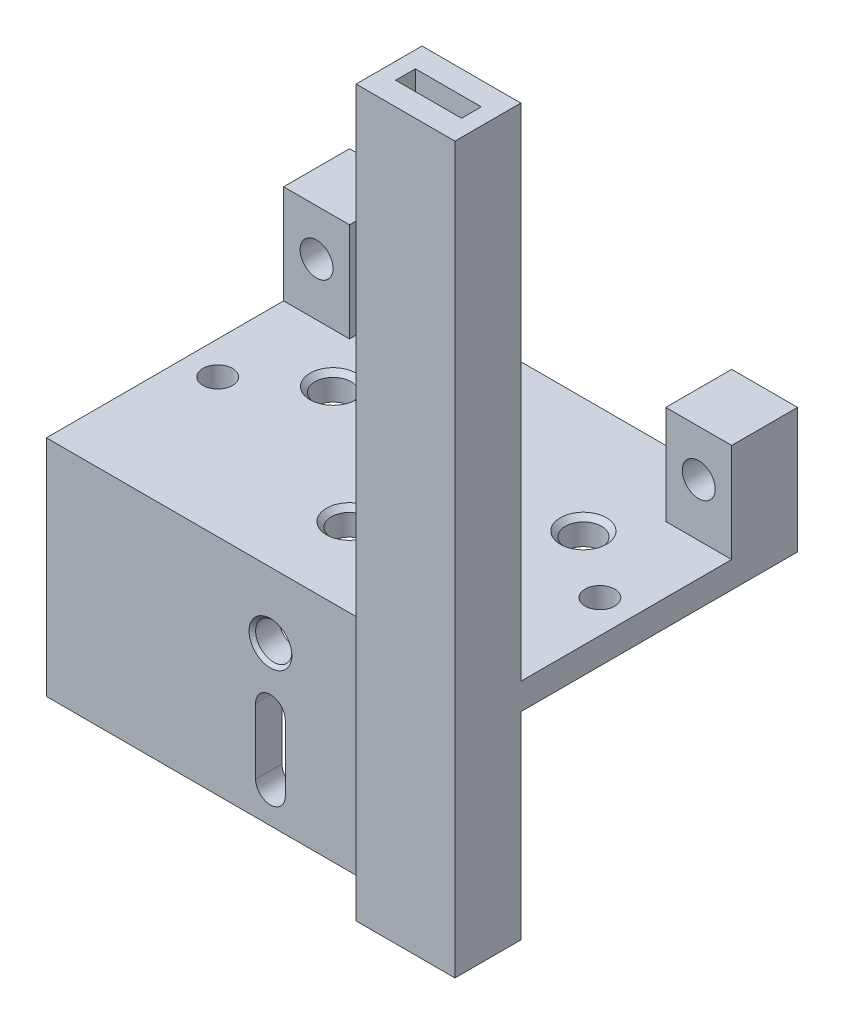
SolidWorks part; units mm, degrees
material "PET"
ref_plane "Front Plane" through (0, 0, 0) normal (0, 0, 1) x (1, 0, 0)
ref_plane "Top Plane" through (0, 0, 0) normal (0, 1, 0) x (1, 0, 0)
ref_plane "Right Plane" through (0, 0, 0) normal (1, 0, 0) x (0, 0, -1)
sketch "Sketch1" plane through (0, 0, 0) normal (0, 1, 0) x (1, 0, 0)
  line L0 (-30, 15) -> (30, 15) construction
  line L2 (-34, 0) -> (-34, 40)
  line L3 (-34, 40) -> (34, 40)
  line L4 (34, 0) -> (34, 40)
  line L5 (0, 0) -> (34, 40) construction
  line L6 (-34, 40) -> (0, 0) construction
  line L7 (-34, 22.5) -> (34, 22.5) construction
  line L8 (-34, 0) -> (-34, -2)
  line L11 (-34, -2) -> (34, -2)
  line L12 (34, -2) -> (34, 0)
  line L13 (-34, 0) -> (34, 0) construction
  line L14 (0, 0) -> (0, 27.8808) construction
  circle A0 centre (-19, 22.5) radius 2.75
  circle A1 centre (19, 22.5) radius 2.75
  circle A3 centre (-29, 15) radius 2.25
  circle A4 centre (29, 15) radius 2.25
  circle A6 centre (0, 6) radius 2.75
  point P0 (0, 0)
  dimension "D5" = 5.5
  dimension "D6" = 5.5
  dimension "D7" = 5.5
  dimension "D8" = 4.5
  dimension "D9" = 4.5
  dimension "D10" = 5
  dimension "D11" = 5
  dimension "D13" = 6
  dimension "D21" = 15
  dimension "D2" = 68
  dimension "D3" = 2
  dimension "D4" = 17.5
  dimension "D12" = 25
  dimension "D17" = 40
  dimension "D18" = 34
  dimension "D20" = 15
extrude "Boss-Extrude1" add sketch "Sketch1" along normal blind 4
sketch "Sketch3" plane through (0, 4, 0) normal (0, 1, 0) x (1, 0, 0)
  line L1 (-34, 40) -> (-24, 40)
  line L2 (-34, 40) -> (-34, 30)
  line L3 (-34, 30) -> (-24, 30)
  line L4 (-24, 40) -> (-24, 30)
  line L5 (34, 40) -> (24, 40)
  line L6 (34, 40) -> (34, 30)
  line L7 (34, 30) -> (24, 30)
  line L8 (24, 40) -> (24, 30)
  dimension "D1" = 10
  dimension "D2" = 10
  dimension "D3" = 10
extrude "Boss-Extrude3" add sketch "Sketch3" along normal blind 15
sketch "Sketch4" plane through (0, 0, -40) normal (0, 0, -1) x (-1, 0, 0)
  line L0 (-24, 19) -> (-34, 5) construction
  line L1 (24, 19) -> (34, 19) construction
  line L2 (24, 19) -> (34, 5) construction
  line L4 (-34, 19) -> (-24, 19) construction
  line L5 (-34, 19) -> (-34, 0) construction
  line L6 (34, 19) -> (34, 0) construction
  circle A0 centre (-29, 12) radius 2.5
  circle A1 centre (29, 12) radius 2.5
  dimension "D3" = 5
  dimension "D4" = 5
  dimension "D5" = 7
  dimension "D1" = 7
extrude "Cut-Extrude1" cut sketch "Sketch4" against normal through all
chamfer "Chamfer1" distance 0.75 angle 45 3 edges at (-19, 4, -19.75) (19, 4, -19.75) (0, 4, -3.25)
sketch "Sketch5" plane through (-34, 0, 0) normal (-1, 0, 0) x (0, 0, 1)
  line L0 (2, 4) -> (2, 0) construction
  line L1 (2, 4) -> (6, 4)
  line L2 (2, 4) -> (2, -30)
  line L3 (2, -30) -> (6, -30)
  line L4 (6, 4) -> (6, -30)
  line L5 (-30, 4) -> (2, 4) construction
  line L6 (-40, 0) -> (2, 0) construction
  dimension "D1" = 30
  dimension "D2" = 4
extrude "Boss-Extrude4" add sketch "Sketch5" against normal up to surface (68 mm away) up to face at (34, 7.6667, -22.6667)
sketch "Sketch7" plane through (0, 0, 2) normal (0, 0, -1) x (-1, 0, 0)
  line L0 (0, -15) -> (0, -25) construction
  line L1 (2.25, -15) -> (2.25, -25)
  line L2 (-2.25, -15) -> (-2.25, -25)
  line L3 (34, 0) -> (-34, 0) construction
  line L4 (0, -6) -> (0, 0) construction
  arc A0 (2.25, -15) -> (-2.25, -15) centre (0, -15) ccw
  arc A1 (-2.25, -25) -> (2.25, -25) centre (0, -25) ccw
  circle A2 centre (0, -6) radius 2.75
  point P3 (0, -20)
  dimension "D1" = 2.25
  dimension "D4" = 5.5
  dimension "D2" = 15
  dimension "D3" = 10
  dimension "D5" = 6
extrude "Cut-Extrude2" cut sketch "Sketch7" against normal through all
chamfer "Chamfer2" distance 0.5 angle 45 1 edges at (0, -3.25, 6)
sketch "Sketch8" plane through (0, -30, 0) normal (0, -1, 0) x (1, 0, 0)
  line L1 (34, 2) -> (19, 2)
  line L2 (34, 2) -> (34, 12)
  line L3 (34, 12) -> (19, 12)
  line L4 (19, 2) -> (19, 12)
  dimension "D1" = 10
  dimension "D2" = 15
extrude "Boss-Extrude5" add sketch "Sketch8" against normal blind 110
sketch "Sketch9" plane through (0, 0, 6) normal (0, 0, 1) x (1, 0, 0)
  line L0 (17, -3) -> (17, -24) construction
  line L1 (19, -3) -> (19, -24)
  line L2 (15, -3) -> (15, -24)
  line L3 (19, 4) -> (19, -30) construction
  line L4 (19, 4) -> (-34, 4) construction
  line L5 (19, -30) -> (-34, -30) construction
  arc A0 (19, -3) -> (15, -3) centre (17, -3) ccw
  arc A1 (15, -24) -> (19, -24) centre (17, -24) ccw
  point P2 (17, -13.5)
  dimension "D1" = 2
  dimension "D3" = 6
  dimension "D2" = 7
extrude "Cut-Extrude3" cut sketch "Sketch9" against normal through all
sketch "Sketch10" plane through (0, 80, 0) normal (0, 1, 0) x (1, 0, 0)
  line L0 (19, -12) -> (34, -2) construction
  line L2 (21.5, -5.5) -> (31.5, -5.5)
  line L3 (21.5, -5.5) -> (21.5, -8.5)
  line L4 (21.5, -8.5) -> (31.5, -8.5)
  line L5 (31.5, -5.5) -> (31.5, -8.5)
  line L6 (21.5, -5.5) -> (31.5, -8.5) construction
  line L7 (21.5, -8.5) -> (31.5, -5.5) construction
  point P4 (26.5, -7)
  dimension "D1" = 10
  dimension "D2" = 3
extrude "Cut-Extrude4" cut sketch "Sketch10" against normal through all
